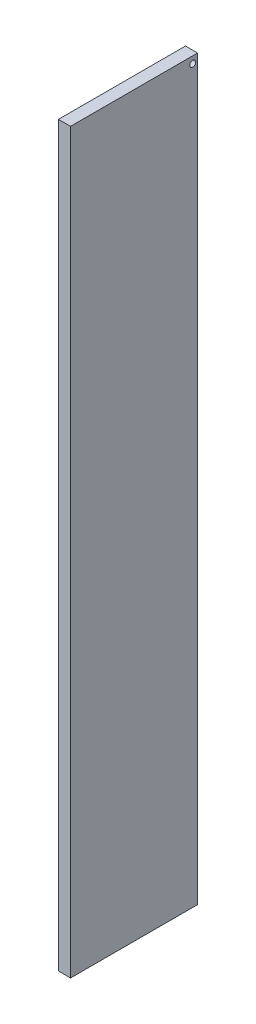
SolidWorks part; units mm, degrees
material "6061 Alloy"
ref_plane "Front Plane" through (0, 0, 0) normal (0, 0, 1) x (1, 0, 0)
ref_plane "Top Plane" through (0, 0, 0) normal (0, 1, 0) x (1, 0, 0)
ref_plane "Right Plane" through (0, 0, 0) normal (1, 0, 0) x (0, 0, -1)
sketch "Sketch1" plane through (0, 0, 0) normal (1, 0, 0) x (0, 0, -1)
  line L1 (-33.3375, 193.548) -> (33.3375, 193.548)
  line L2 (-33.3375, 193.548) -> (-33.3375, -193.548)
  line L3 (-33.3375, -193.548) -> (33.3375, -193.548)
  line L4 (33.3375, 193.548) -> (33.3375, -193.548)
  line L5 (-33.3375, 193.548) -> (33.3375, -193.548) construction
  line L6 (-33.3375, -193.548) -> (33.3375, 193.548) construction
  point P0 (0, 0)
  dimension "D1" = 387.096
  dimension "D2" = 66.675
extrude "Boss-Extrude1" add sketch "Sketch1" along normal blind 6.35
sketch "Sketch2" plane through (6.35, 0, 0) normal (1, 0, 0) x (0, 0, -1)
  circle A0 centre (30.8167, 189.9293) radius 1.5875
extrude "Cut-Extrude1" cut sketch "Sketch2" against normal up to next
